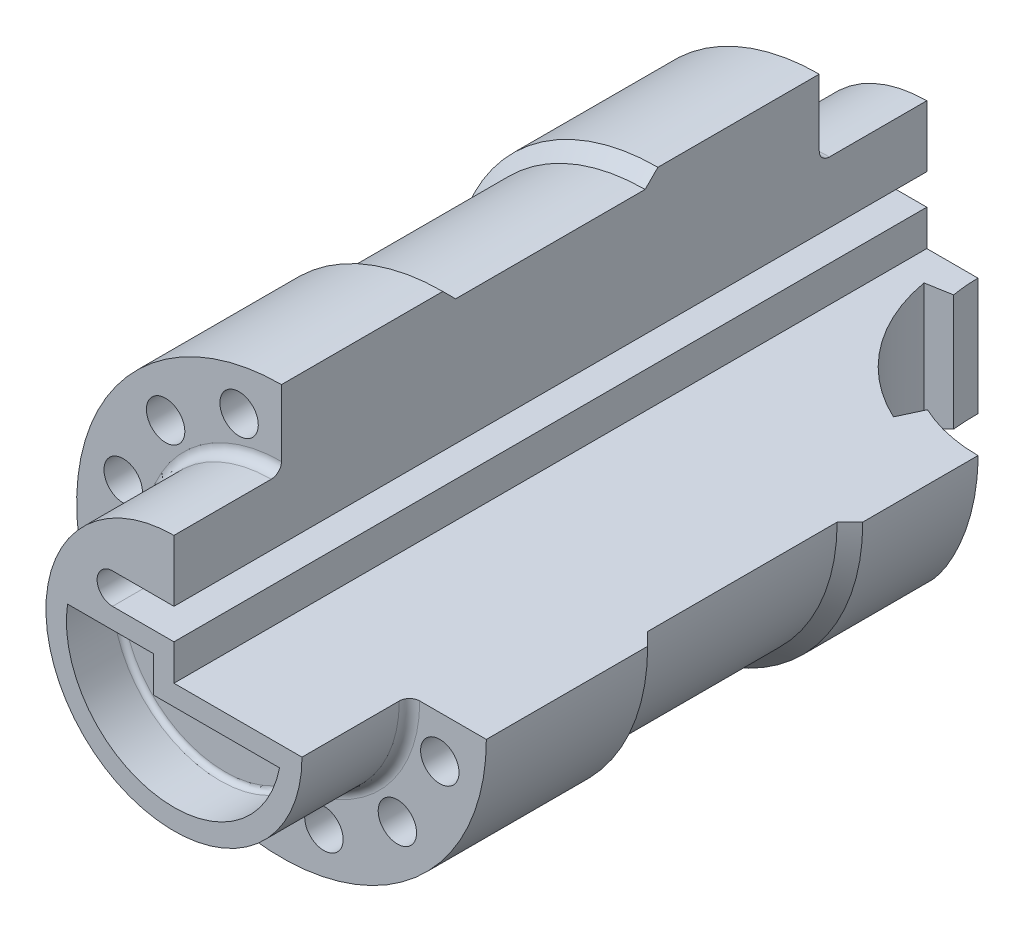
SolidWorks part; units mm, degrees
material "AISI 1020"
ref_plane "Front Plane" through (0, 0, 0) normal (0, 0, 1) x (1, 0, 0)
ref_plane "Top Plane" through (0, 0, 0) normal (0, 1, 0) x (1, 0, 0)
ref_plane "Right Plane" through (0, 0, 0) normal (1, 0, 0) x (0, 0, -1)
sketch "Sketch1" plane through (0, 0, 0) normal (0, 1, 0) x (1, 0, 0)
  circle A1 centre (0, 0) radius 40
  dimension "D2" = 80
extrude "Boss-Extrude1" add sketch "Sketch1" along normal blind 105
sketch "Sketch2" plane through (0, 105, 0) normal (0, 1, 0) x (1, 0, 0)
  circle A0 centre (0, 0) radius 25
  dimension "D1" = 50
extrude "Boss-Extrude2" add sketch "Sketch2" along normal blind 21
sketch "Sketch3" plane through (0, 0, 0) normal (0, -1, 0) x (-1, 0, 0)
  circle A0 centre (0, 0) radius 25
  dimension "D1" = 50
extrude "Boss-Extrude3" add sketch "Sketch3" along normal blind 21
fillet "Fillet1" radius 2 2 edges at (0, 0, -25) (0, 105, 25)
sketch "Sketch4" plane through (0, 0, 0) normal (1, 0, 0) x (0, 0, -1)
  line L0 (40, 73.5) -> (37.5, 71)
  line L2 (40, 0) -> (40, 105) construction
  line L3 (37.5, 71) -> (37.5, 34)
  line L4 (37.5, 34) -> (40, 31.5)
  line L5 (40, 73.5) -> (40, 31.5)
  dimension "D1" = 31.5
  dimension "D2" = 45
  dimension "D3" = 2.5
  dimension "D4" = 45
  dimension "D5" = 31.5
revolve "Cut-Revolve1" cut sketch "Sketch4" angle 360 about axis through (0, 105, 0) along (0, -1, 0)
sketch "Sketch5" plane through (0, -21, 0) normal (0, -1, 0) x (-1, 0, 0)
  line L1 (0, 0) -> (-45.05, 0)
  line L2 (0, 0) -> (0, -42.6157)
  line L3 (0, -42.6157) -> (-45.05, -42.6157)
  line L4 (-45.05, 0) -> (-45.05, -42.6157)
extrude "Cut-Extrude1" cut sketch "Sketch5" against normal through all
sketch "Sketch7" plane through (0, -21, 0) normal (0, -1, 0) x (-1, 0, 0)
  line L0 (12, -10) -> (-12, -10) construction
  line L1 (12, -13) -> (-12, -13)
  line L2 (12, -7) -> (-12, -7)
  line L3 (0, 0) -> (-25, 0) construction
  line L4 (0, -25) -> (0, 0) construction
  arc A0 (12, -13) -> (12, -7) centre (12, -10) ccw
  arc A1 (-12, -7) -> (-12, -13) centre (-12, -10) ccw
  point P2 (0, -10)
  dimension "D1" = 3
  dimension "D2" = 7
  dimension "D3" = 0
  dimension "D4" = 12
extrude "Cut-Extrude2" cut sketch "Sketch7" against normal through all
sketch "Sketch8" plane through (0, -21, 0) normal (0, -1, 0) x (-1, 0, 0)
  line L1 (8.2822, -30.9096) -> (0, 0) construction
  line L2 (0, -27) -> (0, -40) construction
  line L3 (22.6274, -22.6274) -> (0, 0) construction
  circle A0 centre (0, 0) radius 32 construction
  circle A1 centre (8.2822, -30.9096) radius 3.75
  circle A2 centre (-8.2822, -30.9096) radius 3.75
  circle A3 centre (-22.6274, -22.6274) radius 3.75
  circle A4 centre (-30.9096, -8.2822) radius 3.75
  circle A5 centre (-30.9096, 8.2822) radius 3.75
  circle A6 centre (-22.6274, 22.6274) radius 3.75
  circle A7 centre (-8.2822, 30.9096) radius 3.75
  circle A8 centre (8.2822, 30.9096) radius 3.75
  circle A9 centre (22.6274, 22.6274) radius 3.75
  circle A10 centre (30.9096, 8.2822) radius 3.75
  circle A11 centre (30.9096, -8.2822) radius 3.75
  circle A12 centre (22.6274, -22.6274) radius 3.75
  point P32 (0, 0)
  dimension "D1" = 64
  dimension "D3" = 7.5
  dimension "D2" = 15
  dimension "D4" = 12
extrude "Cut-Extrude3" cut sketch "Sketch8" against normal through all
sketch "Sketch9" plane through (0, 0, 0) normal (0, 0, 1) x (1, 0, 0)
  line L0 (40, 105.2761) -> (40, 131.4017) construction
  line L1 (0, 126) -> (25, 126) construction
  line L2 (8.6647, 126) -> (43.3237, 126) construction
  line L4 (40, 126) -> (10.4558, 120.7906)
  line L5 (40, 126) -> (27.3215, 98.8108)
  line L6 (27.3215, 98.8108) -> (25.2084, 94.2792)
  line L7 (10.4558, 120.7906) -> (5.5317, 119.9223)
  circle A0 centre (40, 126) radius 30
  arc A1 (5.5317, 119.9223) -> (25.2084, 94.2792) centre (40, 126) ccw
  line M7 (25, 126) -> (0, 126)
  line M17 (40, 73.5) -> (40, 105)
  line M18 (40, 105) -> (27, 105)
  arc M19 (27, 105) -> (25, 107) centre (27, 107) cw
  line M20 (25, 107) -> (25, 126)
  dimension "D1" = 60
  dimension "D4" = 70
  dimension "D2" = 10
  dimension "D3" = 25
extrude "Cut-Extrude4" cut sketch "Sketch9" against normal through all contours A0 L4 L5 M17 M7 M20 M18 | L5 L4 M20 M19 M18 | L7 A1 L6 A0 | L4 A0 L5 M18 M19 M20 | A0 L4 M7 M20 | L5 A0 M17 M18
sketch "Sketch10" plane through (0, -21, 0) normal (0, -1, 0) x (-1, 0, 0)
  line L0 (4, -3) -> (4, 4)
  line L1 (4, 4) -> (-20.6155, 4)
  line L2 (4, -3) -> (20.7846, -3)
  line L3 (12, -7) -> (0, -7) construction
  line L4 (0, 0) -> (-25, 0) construction
  arc A0 (20.7846, -3) -> (-20.6155, 4) centre (0, 0) ccw
  arc A1 (0, -25) -> (-25, 0) centre (0, 0) ccw construction
  dimension "D1" = 4
  dimension "D2" = 4
  dimension "D3" = 4
  dimension "D4" = 4
extrude "Cut-Extrude5" cut sketch "Sketch10" against normal blind 10
fillet "Fillet2" radius 1 4 edges at (8.3078, -11, -4) (-4, -11, -0.5) (-12.3923, -11, 3) (-3.501, -11, -20.7061)
move or copy body "Body-Move/Copy1" bodies to move or copy 111 copy no rotation origin (0, 52.5, 0) rotation axis (-1, 0, 0) rotation angle 90
equation "\"a\"= 147"
equation "\"b\"= 21"
equation "\"c\"= 31.5"
equation "\"D1@Boss-Extrude2\"=\"b\""
equation "\"D1@Boss-Extrude3\"=\"b\""
equation "\"D1@Sketch4\"=\"c\""
equation "\"D5@Sketch4\"=\"c\""
equation "\"D1@Boss-Extrude1\"=\"a\"-2*\"b\""
